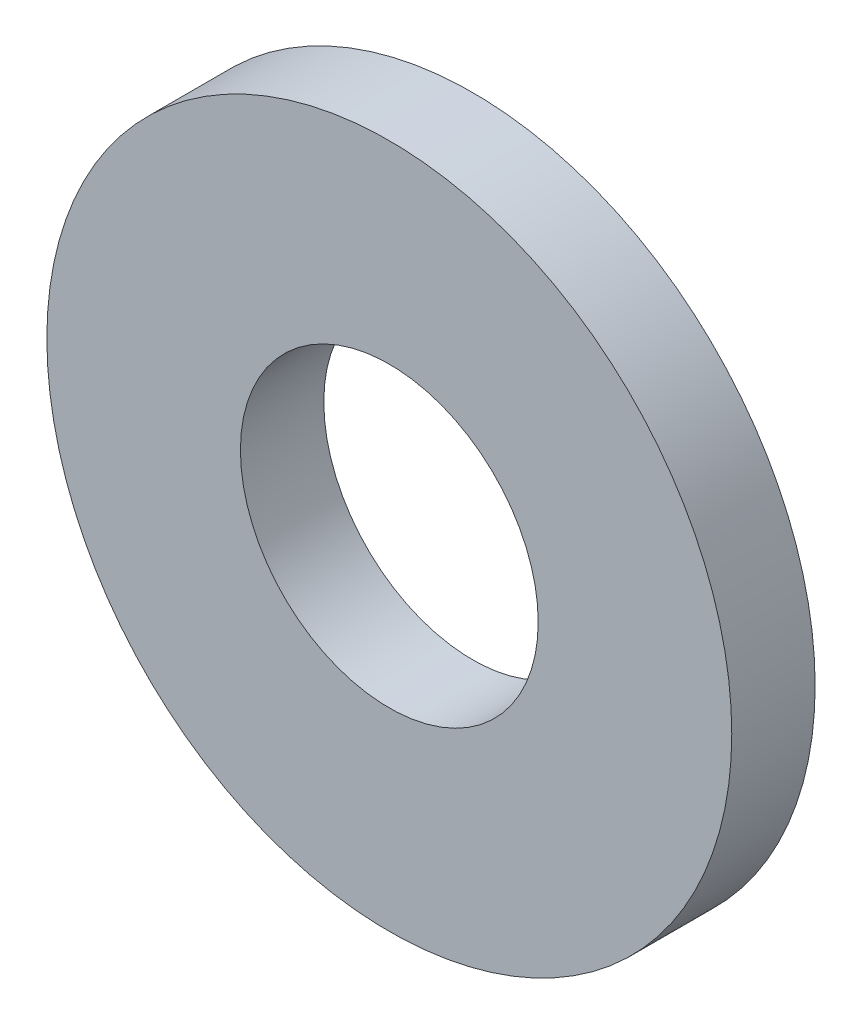
SolidWorks part; units mm, degrees
ref_plane "Plan de face" through (0, 0, 0) normal (0, 0, 1) x (1, 0, 0)
ref_plane "Plan de dessus" through (0, 0, 0) normal (0, 1, 0) x (1, 0, 0)
ref_plane "Plan de droite" through (0, 0, 0) normal (1, 0, 0) x (0, 0, -1)
sketch "Esquisse1" plane through (0, 0, 0) normal (0, 0, 1) x (1, 0, 0)
  circle A0 centre (0, 0) radius 2.875
  circle A1 centre (0, 0) radius 1.25
  dimension "D1" = 5.75
  dimension "D2" = 2.5
extrude "Boss.-Extru.1" add sketch "Esquisse1" along normal blind 0.7
